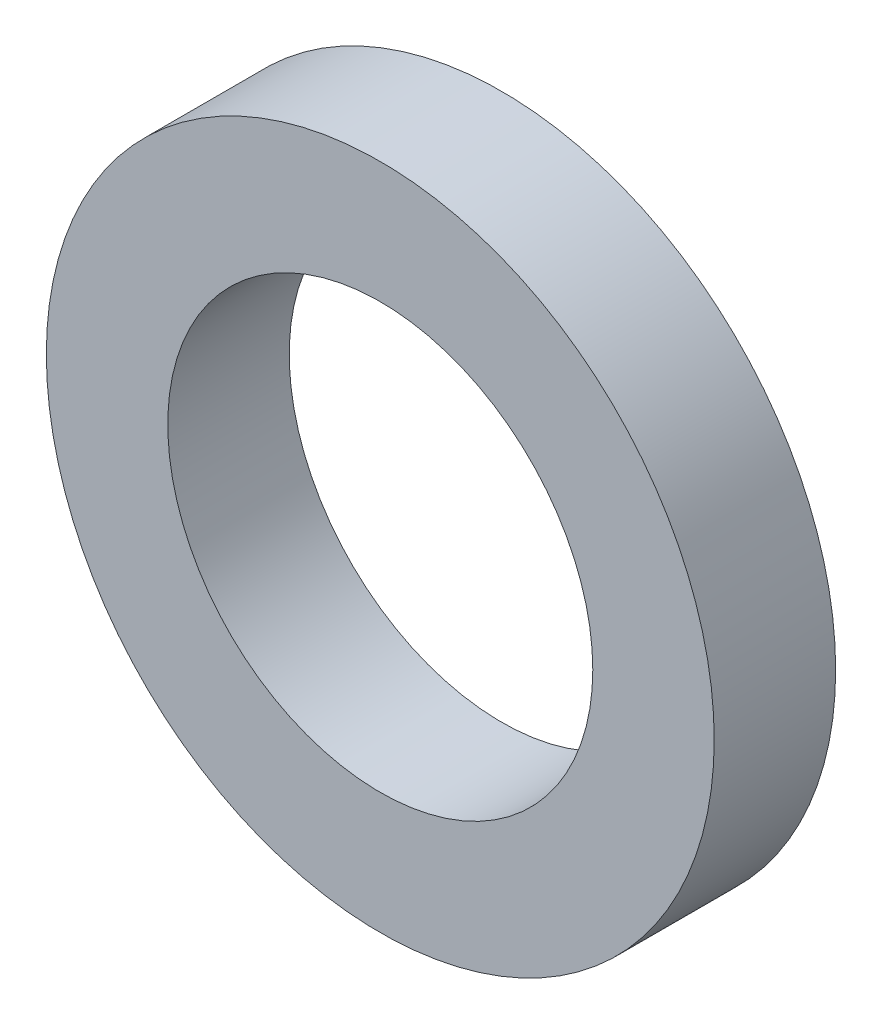
SolidWorks part; units mm, degrees
ref_plane "Front Plane" through (0, 0, 0) normal (0, 0, 1) x (1, 0, 0)
ref_plane "Top Plane" through (0, 0, 0) normal (0, 1, 0) x (1, 0, 0)
ref_plane "Right Plane" through (0, 0, 0) normal (1, 0, 0) x (0, 0, -1)
sketch "Sketch1" plane through (0, 0, 0) normal (0, 0, 1) x (1, 0, 0)
  circle A0 centre (0, 0) radius 27.5
  circle A1 centre (0, 0) radius 17.5
  dimension "D1" = 55
  dimension "D2" = 35
extrude "Boss-Extrude1" add sketch "Sketch1" along normal blind 10
